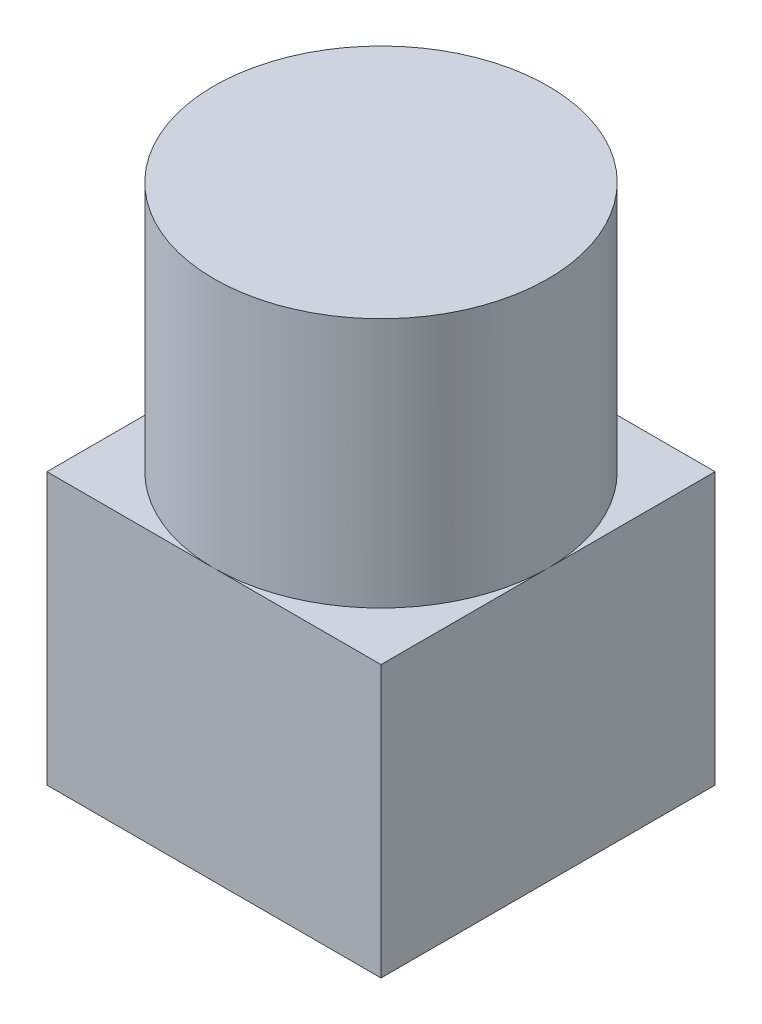
SolidWorks part; units mm, degrees
ref_plane "Płaszczyzna przednia" through (0, 0, 0) normal (0, 0, 1) x (1, 0, 0)
ref_plane "Płaszczyzna górna" through (0, 0, 0) normal (0, 1, 0) x (1, 0, 0)
ref_plane "Płaszczyzna prawa" through (0, 0, 0) normal (1, 0, 0) x (0, 0, -1)
sketch "Szkic1" plane through (0, 0, 0) normal (0, 1, 0) x (1, 0, 0)
  line L1 (-4, -4) -> (4, -4)
  line L2 (-4, -4) -> (-4, 4)
  line L3 (-4, 4) -> (4, 4)
  line L4 (4, -4) -> (4, 4)
  line L5 (-4, -4) -> (4, 4) construction
  line L6 (-4, 4) -> (4, -4) construction
  point P0 (0, 0)
  dimension "D1" = 8
extrude "Dodanie-wyciągnięcie1" add sketch "Szkic1" along normal blind 6.5
sketch "Szkic2" plane through (0, 6.5, 0) normal (0, 1, 0) x (1, 0, 0)
  circle A0 centre (0, 0) radius 4
  dimension "D1" = 8
extrude "Dodanie-wyciągnięcie2" add sketch "Szkic2" along normal blind 6
